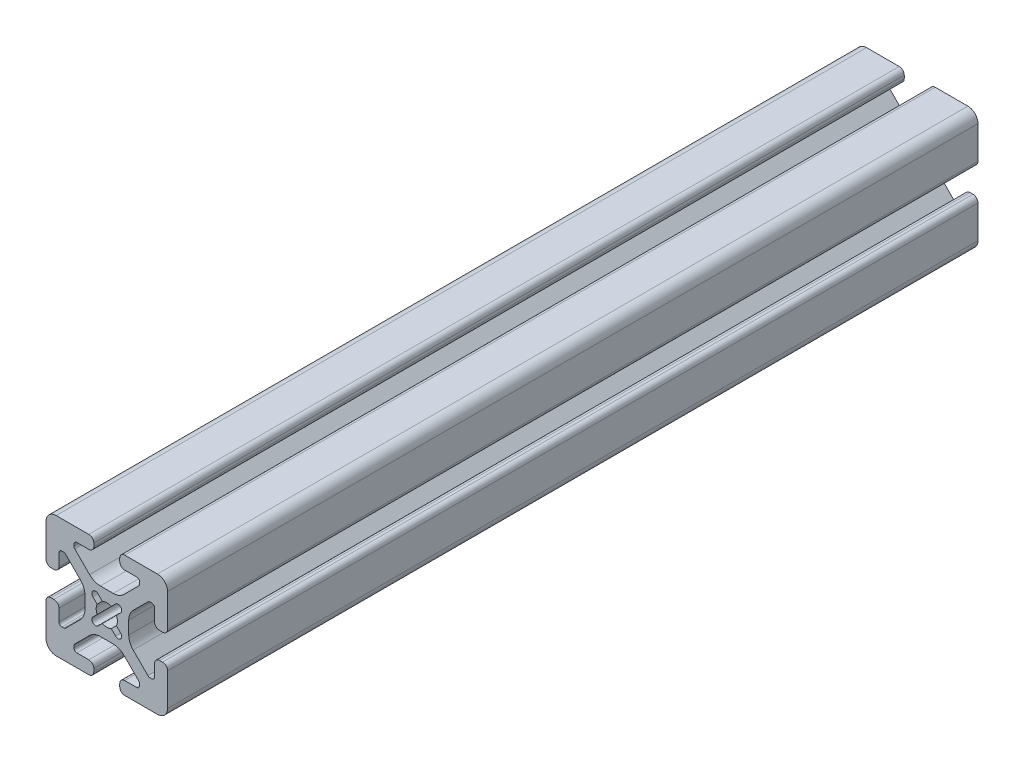
SolidWorks part; units mm, degrees
material "6061-T6 (SS)"
ref_plane "Front Plane" through (0, 0, 0) normal (0, 0, 1) x (1, 0, 0)
ref_plane "Top Plane" through (0, 0, 0) normal (0, 1, 0) x (1, 0, 0)
ref_plane "Right Plane" through (0, 0, 0) normal (1, 0, 0) x (0, 0, -1)
sketch "Sketch1" plane through (0, 0, 0) normal (0, 0, 1) x (1, 0, 0)
  line L0 (4.2456, 2.6398) -> (3.0178, 1.4017)
  line L1 (3.0179, -1.4014) -> (4.3433, -2.7269)
  line L2 (2.7269, -4.3433) -> (1.4014, -3.0179)
  line L3 (-1.4014, -3.0179) -> (-2.7269, -4.3433)
  line L4 (-4.3433, -2.7269) -> (-3.0179, -1.4014)
  line L5 (-3.0179, 1.4014) -> (-4.3433, 2.7269)
  line L6 (-2.7269, 4.3433) -> (-1.4014, 3.0179)
  line L7 (1.4017, 3.0178) -> (2.6398, 4.2456)
  line L8 (14.986, -5.6388) -> (14.986, -9.398)
  line L9 (14.097, -10.287) -> (13.5289, -10.287)
  line L10 (12.9003, -10.0266) -> (8.2608, -5.3872)
  line L11 (6.8697, -2.0285) -> (6.8697, 2.0285)
  line L12 (8.2608, 5.3872) -> (12.9003, 10.0266)
  line L13 (13.5289, 10.287) -> (14.097, 10.287)
  line L14 (14.986, 9.398) -> (14.986, 5.6388)
  line L15 (16.5608, 4.064) -> (17.4752, 4.064)
  line L16 (19.05, 5.6388) -> (19.05, 15.875)
  line L17 (15.875, 19.05) -> (5.6388, 19.05)
  line L18 (4.064, 17.4752) -> (4.064, 16.5608)
  line L19 (5.6388, 14.986) -> (9.398, 14.986)
  line L20 (10.287, 14.097) -> (10.287, 13.5289)
  line L21 (10.0266, 12.9003) -> (5.3872, 8.2608)
  line L22 (2.0285, 6.8697) -> (-2.0285, 6.8697)
  line L23 (-5.3872, 8.2608) -> (-10.0266, 12.9003)
  line L24 (-10.287, 13.5289) -> (-10.287, 14.097)
  line L25 (-9.398, 14.986) -> (-5.6388, 14.986)
  line L26 (-4.064, 16.5608) -> (-4.064, 17.4752)
  line L27 (-5.6388, 19.05) -> (-15.875, 19.05)
  line L28 (-19.05, 15.875) -> (-19.05, 5.6388)
  line L29 (-17.4752, 4.064) -> (-16.5608, 4.064)
  line L30 (-14.986, 5.6388) -> (-14.986, 9.398)
  line L31 (-14.097, 10.287) -> (-13.5289, 10.287)
  line L32 (-12.9003, 10.0266) -> (-8.2608, 5.3872)
  line L33 (-6.8697, 2.0285) -> (-6.8697, -2.0285)
  line L34 (-8.2608, -5.3872) -> (-12.9003, -10.0266)
  line L35 (-13.5289, -10.287) -> (-14.097, -10.287)
  line L36 (-14.986, -9.398) -> (-14.986, -5.6388)
  line L37 (-16.5608, -4.064) -> (-17.4752, -4.064)
  line L38 (-19.05, -5.6388) -> (-19.05, -15.875)
  line L39 (-15.875, -19.05) -> (-5.6388, -19.05)
  line L40 (-4.064, -17.4752) -> (-4.064, -16.5608)
  line L41 (-5.6388, -14.986) -> (-9.398, -14.986)
  line L42 (-10.287, -14.097) -> (-10.287, -13.5289)
  line L43 (-10.0266, -12.9003) -> (-5.3872, -8.2608)
  line L44 (-2.0285, -6.8697) -> (2.0285, -6.8697)
  line L45 (5.3872, -8.2608) -> (10.0266, -12.9003)
  line L46 (10.287, -13.5289) -> (10.287, -14.097)
  line L47 (9.398, -14.986) -> (5.6388, -14.986)
  line L48 (4.064, -16.5608) -> (4.064, -17.4752)
  line L49 (5.6388, -19.05) -> (15.875, -19.05)
  line L50 (19.05, -15.875) -> (19.05, -5.6388)
  line L51 (17.4752, -4.064) -> (16.5608, -4.064)
  arc A0 (4.2456, 2.6398) -> (2.6398, 4.2456) centre (3.5351, 3.5351) ccw
  arc A1 (1.4017, 3.0178) -> (-1.4014, 3.0179) centre (0, 0) ccw
  arc A2 (2.7269, -4.3433) -> (4.3433, -2.7269) centre (3.5351, -3.5351) ccw
  arc A3 (-3.0179, 1.4014) -> (-3.0179, -1.4014) centre (0, 0) ccw
  arc A4 (-4.3433, -2.7269) -> (-2.7269, -4.3433) centre (-3.5351, -3.5351) ccw
  arc A5 (-1.4014, -3.0179) -> (1.4014, -3.0179) centre (0, 0) ccw
  arc A6 (-2.7269, 4.3433) -> (-4.3433, 2.7269) centre (-3.5351, 3.5351) ccw
  arc A8 (16.5608, -4.064) -> (14.986, -5.6388) centre (16.5608, -5.6388) ccw
  arc A9 (14.097, -10.287) -> (14.986, -9.398) centre (14.097, -9.398) ccw
  arc A10 (12.9003, -10.0266) -> (13.5289, -10.287) centre (13.5289, -9.398) ccw
  arc A11 (6.8697, -2.0285) -> (8.2608, -5.3872) centre (11.6195, -2.0285) ccw
  arc A12 (8.2608, 5.3872) -> (6.8697, 2.0285) centre (11.6195, 2.0285) ccw
  arc A13 (13.5289, 10.287) -> (12.9003, 10.0266) centre (13.5289, 9.398) ccw
  arc A14 (14.986, 9.398) -> (14.097, 10.287) centre (14.097, 9.398) ccw
  arc A15 (14.986, 5.6388) -> (16.5608, 4.064) centre (16.5608, 5.6388) ccw
  arc A16 (17.4752, 4.064) -> (19.05, 5.6388) centre (17.4752, 5.6388) ccw
  arc A17 (19.05, 15.875) -> (15.875, 19.05) centre (15.875, 15.875) ccw
  arc A18 (5.6388, 19.05) -> (4.064, 17.4752) centre (5.6388, 17.4752) ccw
  arc A19 (4.064, 16.5608) -> (5.6388, 14.986) centre (5.6388, 16.5608) ccw
  arc A20 (10.287, 14.097) -> (9.398, 14.986) centre (9.398, 14.097) ccw
  arc A21 (10.0266, 12.9003) -> (10.287, 13.5289) centre (9.398, 13.5289) ccw
  arc A22 (2.0285, 6.8697) -> (5.3872, 8.2608) centre (2.0285, 11.6195) ccw
  arc A23 (-5.3872, 8.2608) -> (-2.0285, 6.8697) centre (-2.0285, 11.6195) ccw
  arc A24 (-10.287, 13.5289) -> (-10.0266, 12.9003) centre (-9.398, 13.5289) ccw
  arc A25 (-9.398, 14.986) -> (-10.287, 14.097) centre (-9.398, 14.097) ccw
  arc A26 (-5.6388, 14.986) -> (-4.064, 16.5608) centre (-5.6388, 16.5608) ccw
  arc A27 (-4.064, 17.4752) -> (-5.6388, 19.05) centre (-5.6388, 17.4752) ccw
  arc A28 (-15.875, 19.05) -> (-19.05, 15.875) centre (-15.875, 15.875) ccw
  arc A29 (-19.05, 5.6388) -> (-17.4752, 4.064) centre (-17.4752, 5.6388) ccw
  arc A30 (-16.5608, 4.064) -> (-14.986, 5.6388) centre (-16.5608, 5.6388) ccw
  arc A31 (-14.097, 10.287) -> (-14.986, 9.398) centre (-14.097, 9.398) ccw
  arc A32 (-12.9003, 10.0266) -> (-13.5289, 10.287) centre (-13.5289, 9.398) ccw
  arc A33 (-6.8697, 2.0285) -> (-8.2608, 5.3872) centre (-11.6195, 2.0285) ccw
  arc A34 (-8.2608, -5.3872) -> (-6.8697, -2.0285) centre (-11.6195, -2.0285) ccw
  arc A35 (-13.5289, -10.287) -> (-12.9003, -10.0266) centre (-13.5289, -9.398) ccw
  arc A36 (-14.986, -9.398) -> (-14.097, -10.287) centre (-14.097, -9.398) ccw
  arc A37 (-14.986, -5.6388) -> (-16.5608, -4.064) centre (-16.5608, -5.6388) ccw
  arc A38 (-17.4752, -4.064) -> (-19.05, -5.6388) centre (-17.4752, -5.6388) ccw
  arc A39 (-19.05, -15.875) -> (-15.875, -19.05) centre (-15.875, -15.875) ccw
  arc A40 (-5.6388, -19.05) -> (-4.064, -17.4752) centre (-5.6388, -17.4752) ccw
  arc A41 (-4.064, -16.5608) -> (-5.6388, -14.986) centre (-5.6388, -16.5608) ccw
  arc A42 (-10.287, -14.097) -> (-9.398, -14.986) centre (-9.398, -14.097) ccw
  arc A43 (-10.0266, -12.9003) -> (-10.287, -13.5289) centre (-9.398, -13.5289) ccw
  arc A44 (-2.0285, -6.8697) -> (-5.3872, -8.2608) centre (-2.0285, -11.6195) ccw
  arc A45 (5.3872, -8.2608) -> (2.0285, -6.8697) centre (2.0285, -11.6195) ccw
  arc A46 (10.287, -13.5289) -> (10.0266, -12.9003) centre (9.398, -13.5289) ccw
  arc A47 (9.398, -14.986) -> (10.287, -14.097) centre (9.398, -14.097) ccw
  arc A48 (5.6388, -14.986) -> (4.064, -16.5608) centre (5.6388, -16.5608) ccw
  arc A49 (4.064, -17.4752) -> (5.6388, -19.05) centre (5.6388, -17.4752) ccw
  arc A50 (15.875, -19.05) -> (19.05, -15.875) centre (15.875, -15.875) ccw
  arc A51 (19.05, -5.6388) -> (17.4752, -4.064) centre (17.4752, -5.6388) ccw
  arc A52 (3.0179, -1.4014) -> (3.0178, 1.4017) centre (0, 0) ccw
  dimension "D1" = 6.6548
extrude "Extrude1" add sketch "Sketch1" against normal blind 254
